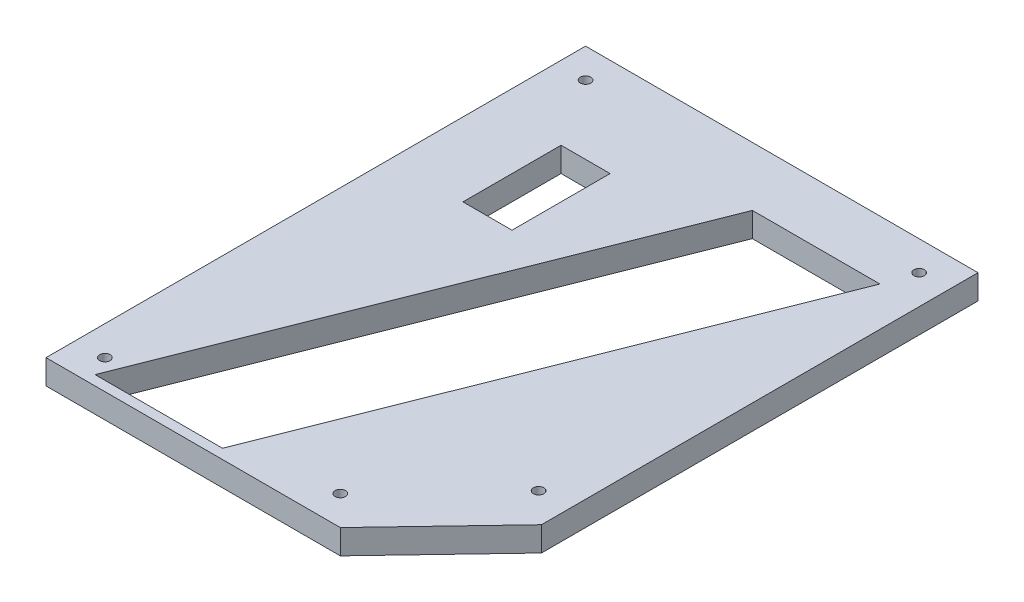
SolidWorks part; units mm, degrees
ref_plane "Front Plane" through (0, 0, 0) normal (0, 0, 1) x (1, 0, 0)
ref_plane "Top Plane" through (0, 0, 0) normal (0, 1, 0) x (1, 0, 0)
ref_plane "Right Plane" through (0, 0, 0) normal (1, 0, 0) x (0, 0, -1)
sketch "Sketch1" plane through (0, 0, 0) normal (0, 1, 0) x (1, 0, 0)
  line L1 (-50.8, -63.5) -> (50.8, -63.5)
  line L2 (-50.8, -63.5) -> (-50.8, 76.2)
  line L3 (-50.8, 76.2) -> (50.8, 76.2)
  line L4 (50.8, -63.5) -> (50.8, 76.2)
  point P7 (4.7349, -13.5875)
  dimension "D1" = 101.6
  dimension "D2" = 139.7
  dimension "D3" = 50.8
  dimension "D4" = 63.5
extrude "Boss-Extrude1" add sketch "Sketch1" along normal blind 6.35
sketch "Sketch3" plane through (0, 6.35, 0) normal (0, 1, 0) x (1, 0, 0)
  line L0 (0, -63.5) -> (0, 76.2) construction
  line L1 (-50.8, -63.5) -> (50.8, -63.5) construction
  line L2 (50.8, 76.2) -> (-50.8, 76.2) construction
  line L3 (0, 30.226) -> (31.75, 57.404) construction
  line L4 (50.8, -63.5) -> (50.8, 76.2) construction
  line L5 (50.8, 0) -> (-50.8, 0) construction
  line L6 (-50.8, 76.2) -> (-50.8, -63.5) construction
  line L7 (-1.4866, 31.9626) -> (30.2634, 59.1406)
  line L8 (1.4866, 28.4894) -> (33.2366, 55.6674)
  line L9 (0, -30.226) -> (-31.75, -57.404) construction
  line L10 (1.4866, -31.9626) -> (-30.2634, -59.1406)
  line L11 (-1.4866, -28.4894) -> (-33.2366, -55.6674)
  arc A0 (-1.4866, 31.9626) -> (1.4866, 28.4894) centre (0, 30.226) ccw
  arc A1 (33.2366, 55.6674) -> (30.2634, 59.1406) centre (31.75, 57.404) ccw
  arc A2 (1.4866, -31.9626) -> (-1.4866, -28.4894) centre (0, -30.226) ccw
  arc A3 (-33.2366, -55.6674) -> (-30.2634, -59.1406) centre (-31.75, -57.404) ccw
  point P15 (15.875, 43.815)
  point P24 (-15.875, -43.815)
  point P29 (0, 0)
  dimension "D1" = 30.226
  dimension "D2" = 27.178
  dimension "D3" = 31.75
  dimension "D4" = 4.572
  dimension "D5" = 2
extrude "Cut-Extrude1" cut sketch "Sketch3" against normal through all
sketch "Sketch7" plane through (0, 6.35, 0) normal (0, 1, 0) x (1, 0, 0)
  line L0 (50.8, -36.8137) -> (25.4, -63.5)
  line L1 (50.8, -63.5) -> (50.8, 76.2) construction
  line L2 (-50.8, -63.5) -> (50.8, -63.5) construction
  dimension "D1" = 25.4
  dimension "D2" = 26.6863
extrude "Cut-Extrude4" cut sketch "Sketch7" against normal blind 6.35 and the other way through all
sketch "Sketch10" plane through (0, 6.35, 0) normal (0, 1, 0) x (1, 0, 0)
  line L0 (-40.64, -60.96) -> (-7.62, -60.96)
  line L1 (-40.64, -60.96) -> (7.62, 60.96)
  line L2 (-7.62, -60.96) -> (40.64, 60.96)
  line L3 (7.62, 60.96) -> (40.64, 60.96)
  point P7 (-77.7142, 7.6224)
  dimension "D1" = 7.62
  dimension "D2" = 7.62
  dimension "D3" = 60.96
  dimension "D4" = 60.96
  dimension "D5" = 33.02
extrude "Cut-Extrude5" cut sketch "Sketch10" against normal blind 6.35
sketch "Sketch11" plane through (0, 6.35, 0) normal (0, 1, 0) x (1, 0, 0)
  line L0 (-50.8, 76.2) -> (-50.8, -63.5) construction
  line L1 (-31.75, 25.4) -> (-19.05, 25.4)
  line L2 (-31.75, 25.4) -> (-31.75, 50.8)
  line L3 (-31.75, 50.8) -> (-19.05, 50.8)
  line L4 (-19.05, 25.4) -> (-19.05, 50.8)
  line L5 (-31.75, 25.4) -> (-19.05, 50.8) construction
  line L6 (-31.75, 50.8) -> (-19.05, 25.4) construction
  line L8 (50.8, 76.2) -> (-50.8, 76.2) construction
  point P0 (-25.4, 38.1)
  point P9 (-23.4904, 76.2)
  point P10 (-147.011, 86.1196)
  dimension "D1" = 25.4
  dimension "D2" = 12.7
  dimension "D3" = 25.4
  dimension "D4" = 38.1
extrude "Cut-Extrude6" cut sketch "Sketch11" against normal blind 6.35
sketch "Sketch12" plane through (0, 6.35, 0) normal (0, 1, 0) x (1, 0, 0)
  line L0 (-50.8, 76.2) -> (-50.8, -63.5) construction
  line L1 (38.1, -50.1568) -> (0, -13.8933) construction
  line L2 (50.8, 76.2) -> (-50.8, 76.2) construction
  line L3 (0, 76.2) -> (0, -63.5) construction
  line L4 (-50.8, -63.5) -> (25.4, -63.5) construction
  line L5 (-50.8, 6.35) -> (50.8, 6.35) construction
  line L6 (50.8, -36.8137) -> (50.8, 76.2) construction
  line L7 (25.4, -63.5) -> (50.8, -36.8137) construction
  circle A0 centre (-43.18, 68.58) radius 1.3526
  circle A1 centre (43.18, 68.58) radius 1.3526
  circle A2 centre (-43.18, -55.88) radius 1.3526
  circle A3 centre (17.78, -55.88) radius 1.3526
  circle A4 centre (42.8132, -29.5791) radius 1.3526
  dimension "D1" = 2.7051
  dimension "D4" = 2.7051
  dimension "D6" = 33.02
  dimension "D2" = 7.62
  dimension "D3" = 7.62
  dimension "D5" = 7.62
extrude "Cut-Extrude7" cut sketch "Sketch12" against normal through all
